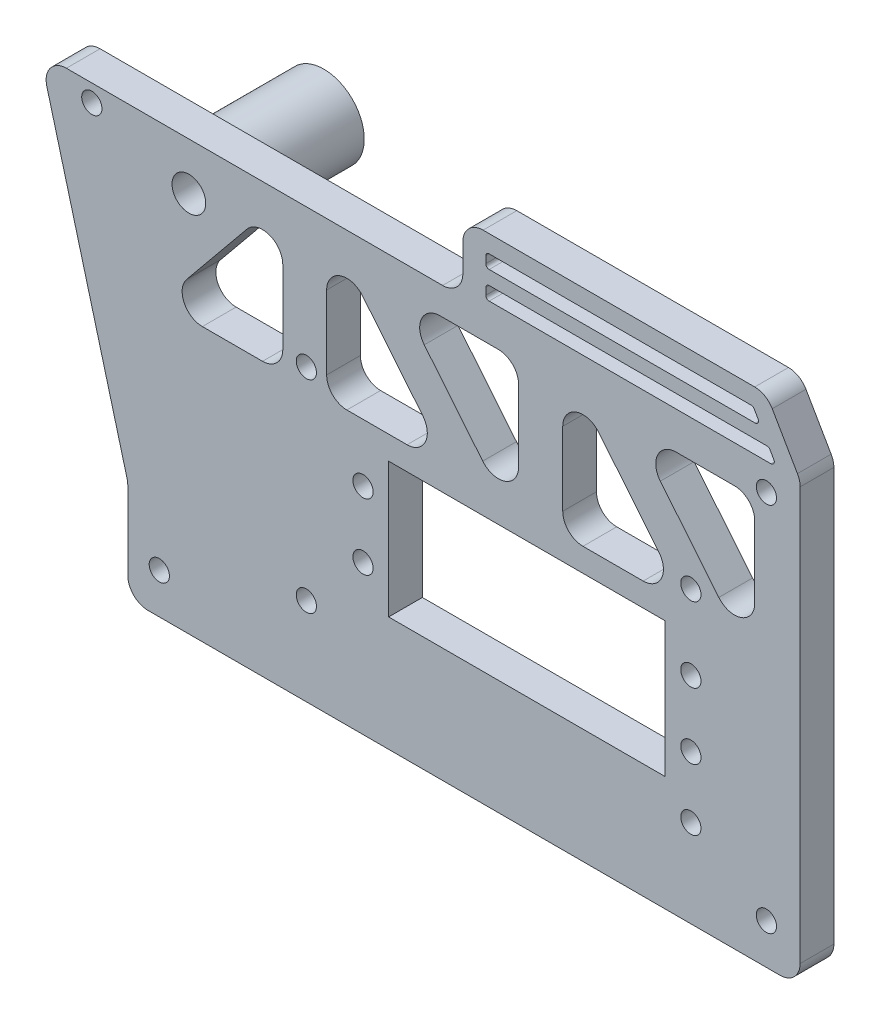
SolidWorks part; units mm, degrees
ref_plane "前视基准面" through (0, 0, 0) normal (0, 0, 1) x (1, 0, 0)
ref_plane "上视基准面" through (0, 0, 0) normal (0, 1, 0) x (1, 0, 0)
ref_plane "右视基准面" through (0, 0, 0) normal (1, 0, 0) x (0, 0, -1)
sketch "草图1" plane through (0, 0, 0) normal (0, 0, 1) x (1, 0, 0)
  line L0 (9.9753, -26.4766) -> (9.9753, 16.164) construction
  line L2 (50.4753, 32.1122) -> (50.4753, -29.084)
  line L3 (47.4753, -32.084) -> (-46.1994, -32.084)
  line L4 (-49.1994, -17.4789) -> (-49.1994, -29.084)
  line L5 (50.4753, 32.916) -> (-49.1994, -32.084) construction
  line L6 (50.4753, -32.084) -> (-49.5143, 31.4731) construction
  line L7 (30.4753, 4.916) -> (-10.5247, 4.916)
  line L8 (30.4753, 4.916) -> (30.4753, -15.084)
  line L9 (30.4753, -15.084) -> (-10.5247, -15.084)
  line L10 (-10.5247, 4.916) -> (-10.5247, -15.084)
  line L11 (30.4753, 4.916) -> (-10.5247, -15.084) construction
  line L12 (30.4753, -15.084) -> (-10.5247, 4.916) construction
  line L13 (34.2753, 10.916) -> (34.2753, -18.8676) construction
  line L14 (47.4759, -5.084) -> (-17.836, -5.084) construction
  line L15 (50.0734, 33.6122) -> (46.3413, 40.0763)
  line L16 (-49.3016, -16.7025) -> (-61.1984, 27.6966)
  line L17 (43.7433, 41.5763) -> (3.4753, 41.5763)
  line L18 (0.4753, 38.5763) -> (0.4753, 34.4731)
  line L19 (-2.5247, 31.4731) -> (-58.3006, 31.4731)
  line L20 (43.7433, 24.3889) -> (43.7433, 13.7931)
  line L21 (38.4214, 11.8934) -> (29.7521, 22.4892)
  line L22 (32.074, 27.3889) -> (40.7433, 27.3889)
  line L26 (27.2056, 8.3889) -> (18.2829, 8.3889)
  line L27 (29.5275, 13.2886) -> (20.6048, 24.1942)
  line L28 (15.2829, 11.3889) -> (15.2829, 22.2945)
  line L32 (-2.926, 27.3889) -> (5.7433, 27.3889)
  line L33 (8.7433, 24.3889) -> (8.7433, 13.7931)
  line L34 (3.4214, 11.8934) -> (-5.2479, 22.4892)
  line L36 (-7.7944, 8.3889) -> (-16.7171, 8.3889)
  line L37 (-5.4725, 13.2886) -> (-14.3952, 24.1942)
  line L50 (-72.926, 27.3889) -> (-64.2567, 27.3889) [skipped]
  line L51 (-66.5786, 11.8934) -> (-75.2479, 22.4892) [skipped]
  line L52 (-89.7171, 11.3889) -> (-89.7171, 22.2945) [skipped]
  line L53 (-77.7944, 8.3889) -> (-86.7171, 8.3889) [skipped]
  line L54 (-75.4725, 13.2886) -> (-84.3952, 24.1942) [skipped]
  line L55 (-61.2567, 24.3889) -> (-61.2567, 13.7931) [skipped]
  line L56 (-31.5786, 11.8934) -> (-40.2479, 22.4892) [skipped]
  line L57 (-26.2567, 24.3889) -> (-26.2567, 13.7931) [skipped]
  line L58 (-37.926, 27.3889) -> (-29.2567, 27.3889) [skipped]
  line L59 (-40.4725, 13.2886) -> (-49.3952, 24.1942) [skipped]
  line L60 (-42.7944, 8.3889) -> (-51.7171, 8.3889) [skipped]
  line L61 (-54.7171, 11.3889) -> (-54.7171, 22.2945) [skipped]
  line L62 (-22.9671, 37.1735) -> (-22.9671, -3.2842) construction
  line L64 (-38.1398, 8.3889) -> (-29.2171, 8.3889)
  line L65 (-40.4617, 13.2886) -> (-31.539, 24.1942)
  line L70 (43.6567, 38.7263) -> (44.234, 37.7263)
  line L72 (3.8772, 38.4763) -> (3.8772, 37.4763)
  line L75 (45.5678, 34.916) -> (4.3772, 34.916)
  line L76 (3.8772, 34.416) -> (3.8772, 33.416)
  line L77 (4.3772, 32.916) -> (46.1452, 32.916)
  line L78 (46.0009, 34.666) -> (46.5782, 33.666)
  line L79 (43.2237, 38.9763) -> (4.3772, 38.9763)
  line L80 (43.801, 36.9763) -> (4.3772, 36.9763)
  line L81 (45.4753, -35.1949) -> (45.4753, 65.7469) construction
  line L82 (58.2283, -26.084) -> (-68.4601, -26.084) construction
  line L83 (45.4753, 28.916) -> (-107.4561, 28.916) construction
  line L84 (40.3368, 10.916) -> (-58.6948, 10.916) construction
  line L85 (-19.7171, 11.3889) -> (-19.7171, 22.2945) [skipped]
  line L86 (-19.7171, 11.3889) -> (-19.7171, 22.2945)
  line L87 (-26.2171, 11.3889) -> (-26.2171, 22.2945)
  line L88 (-22.7247, 10.916) -> (-22.7247, -23.7298) construction
  circle A0 centre (34.2753, -0.184) radius 1.5
  circle A2 centre (34.2753, -9.984) radius 1.5
  circle A3 centre (-14.3247, -9.984) radius 1.5
  circle A4 centre (-14.3247, -0.184) radius 1.5
  arc A5 (-46.1994, -32.084) -> (-49.1994, -29.084) centre (-46.1994, -29.084) cw
  arc A6 (50.4753, -29.084) -> (47.4753, -32.084) centre (47.4753, -29.084) cw
  arc A7 (50.0734, 33.6122) -> (50.4753, 32.1122) centre (47.4753, 32.1122) cw
  arc A8 (46.3413, 40.0763) -> (43.7433, 41.5763) centre (43.7433, 38.5763) ccw
  arc A9 (-49.3016, -16.7025) -> (-49.1994, -17.4789) centre (-52.1994, -17.4789) cw
  arc A10 (-58.3006, 31.4731) -> (-61.1984, 27.6966) centre (-58.3006, 28.4731) ccw
  arc A11 (0.4753, 34.4731) -> (-2.5247, 31.4731) centre (-2.5247, 34.4731) cw
  arc A12 (3.4753, 41.5763) -> (0.4753, 38.5763) centre (3.4753, 38.5763) ccw
  arc A13 (15.2829, 22.2945) -> (20.6048, 24.1942) centre (18.2829, 22.2945) cw
  arc A14 (18.2829, 8.3889) -> (15.2829, 11.3889) centre (18.2829, 11.3889) cw
  arc A15 (27.2056, 8.3889) -> (29.5275, 13.2886) centre (27.2056, 11.3889) ccw
  arc A16 (43.7433, 13.7931) -> (38.4214, 11.8934) centre (40.7433, 13.7931) cw
  arc A17 (29.7521, 22.4892) -> (32.074, 27.3889) centre (32.074, 24.3889) cw
  arc A18 (43.7433, 24.3889) -> (40.7433, 27.3889) centre (40.7433, 24.3889) ccw
  arc A22 (8.7433, 24.3889) -> (5.7433, 27.3889) centre (5.7433, 24.3889) ccw
  arc A23 (8.7433, 13.7931) -> (3.4214, 11.8934) centre (5.7433, 13.7931) cw
  arc A24 (-5.2479, 22.4892) -> (-2.926, 27.3889) centre (-2.926, 24.3889) cw
  arc A25 (-19.7171, 22.2945) -> (-14.3952, 24.1942) centre (-16.7171, 22.2945) cw
  arc A26 (-16.7171, 8.3889) -> (-19.7171, 11.3889) centre (-16.7171, 11.3889) cw
  arc A27 (-7.7944, 8.3889) -> (-5.4725, 13.2886) centre (-7.7944, 11.3889) ccw
  arc A40 (-61.2567, 13.7931) -> (-66.5786, 11.8934) centre (-64.2567, 13.7931) cw [skipped]
  arc A41 (-75.2479, 22.4892) -> (-72.926, 27.3889) centre (-72.926, 24.3889) cw [skipped]
  arc A42 (-89.7171, 22.2945) -> (-84.3952, 24.1942) centre (-86.7171, 22.2945) cw [skipped]
  arc A43 (-86.7171, 8.3889) -> (-89.7171, 11.3889) centre (-86.7171, 11.3889) cw [skipped]
  arc A44 (-77.7944, 8.3889) -> (-75.4725, 13.2886) centre (-77.7944, 11.3889) ccw [skipped]
  arc A45 (-61.2567, 24.3889) -> (-64.2567, 27.3889) centre (-64.2567, 24.3889) ccw [skipped]
  arc A46 (-26.2567, 13.7931) -> (-31.5786, 11.8934) centre (-29.2567, 13.7931) cw [skipped]
  arc A47 (-40.2479, 22.4892) -> (-37.926, 27.3889) centre (-37.926, 24.3889) cw [skipped]
  arc A48 (-26.2567, 24.3889) -> (-29.2567, 27.3889) centre (-29.2567, 24.3889) ccw [skipped]
  arc A49 (-42.7944, 8.3889) -> (-40.4725, 13.2886) centre (-42.7944, 11.3889) ccw [skipped]
  arc A50 (-54.7171, 22.2945) -> (-49.3952, 24.1942) centre (-51.7171, 22.2945) cw [skipped]
  arc A51 (-51.7171, 8.3889) -> (-54.7171, 11.3889) centre (-51.7171, 11.3889) cw [skipped]
  arc A52 (-29.2171, 8.3889) -> (-26.2171, 11.3889) centre (-29.2171, 11.3889) ccw
  arc A53 (-38.1398, 8.3889) -> (-40.4617, 13.2886) centre (-38.1398, 11.3889) cw
  arc A54 (-26.2171, 22.2945) -> (-31.539, 24.1942) centre (-29.2171, 22.2945) ccw
  arc A55 (4.3772, 38.9763) -> (3.8772, 38.4763) centre (4.3772, 38.4763) ccw
  arc A56 (3.8772, 37.4763) -> (4.3772, 36.9763) centre (4.3772, 37.4763) ccw
  arc A57 (4.3772, 34.916) -> (3.8772, 34.416) centre (4.3772, 34.416) ccw
  arc A58 (3.8772, 33.416) -> (4.3772, 32.916) centre (4.3772, 33.416) ccw
  arc A59 (46.1452, 32.916) -> (46.5782, 33.666) centre (46.1452, 33.416) ccw
  arc A60 (45.5678, 34.916) -> (46.0009, 34.666) centre (45.5678, 34.416) cw
  arc A61 (43.801, 36.9763) -> (44.234, 37.7263) centre (43.801, 37.4763) ccw
  arc A62 (43.2237, 38.9763) -> (43.6567, 38.7263) centre (43.2237, 38.4763) cw
  circle A64 centre (45.4753, -26.084) radius 1.5
  circle A65 centre (45.4753, 28.916) radius 1.5
  circle A66 centre (-44.5247, -26.084) radius 1.5
  circle A68 centre (-54.5247, 28.916) radius 1.5
  circle A69 centre (34.2753, 10.916) radius 1.5
  circle A70 centre (-22.7247, 10.916) radius 1.5
  circle A71 centre (34.2753, -19.084) radius 1.5
  circle A72 centre (-22.7247, -19.084) radius 1.5
  point P0 (0, 0)
  point P6 (9.9753, -5.084)
  point P41 (45.4753, 41.5763)
  point P44 (-49.1994, -17.084)
  point P66 (43.7433, 5.3889)
  point P69 (25.7433, 27.3889)
  point P72 (43.7433, 27.3889)
  point P107 (6.4753, 35.5763)
  point P112 (41.4753, 33.5763)
  point P113 (3.8772, 40.0763)
  point P115 (41.4753, 35.5763)
  point P189 (42.8772, 40.0763)
  dimension "D7" = 3
  dimension "D8" = 3
  dimension "D16" = 3
  dimension "D21" = 3
  dimension "D27" = 2.6
  dimension "D28" = 0.5
  dimension "D29" = 3
  dimension "D32" = 3
  dimension "D34" = 3
  dimension "D36" = 3
  dimension "D38" = 3
  dimension "D40" = 3
  dimension "D23" = 3
  dimension "D43" = 3
  dimension "D1" = 100
  dimension "D2" = 65
  dimension "D3" = 41
  dimension "D4" = 20
  dimension "D5" = 20
  dimension "D6" = 17
  dimension "D9" = 9.8
  dimension "D10" = 4.9
  dimension "D11" = 24.3
  dimension "D12" = 10
  dimension "D13" = 50
  dimension "D14" = 15
  dimension "D15" = 15
  dimension "D17" = 22
  dimension "D18" = 2
  dimension "D19" = 3
  dimension "D20" = 6
  dimension "D24" = 3
  dimension "D25" = 39
  dimension "D26" = 2
  dimension "D30" = 5
  dimension "D31" = 6
  dimension "D33" = 55
  dimension "D35" = 90
  dimension "D37" = 100
  dimension "D39" = 6
  dimension "D41" = 57
  dimension "D42" = 30
  dimension "D44" = 30
  dimension "D22" = 4
extrude "凸台-拉伸1" add sketch "草图1" along normal blind 5
sketch "草图2" plane through (0, 0, 0) normal (0, 0, -1) x (-1, 0, 0)
  circle A0 centre (40.1403, 24.4491) radius 6
  circle A1 centre (40.1403, 24.4491) radius 4
  dimension "D1" = 12
  dimension "D3" = 8
  dimension "D2" = 47
extrude "凸台-拉伸2" add sketch "草图2" along normal blind 15
sketch "草图3" plane through (0, 0, 0) normal (0, 0, -1) x (-1, 0, 0)
  circle A0 centre (40.1403, 24.4491) radius 2.5
  dimension "D1" = 5
extrude "切除-拉伸1" cut sketch "草图3" against normal up to next
